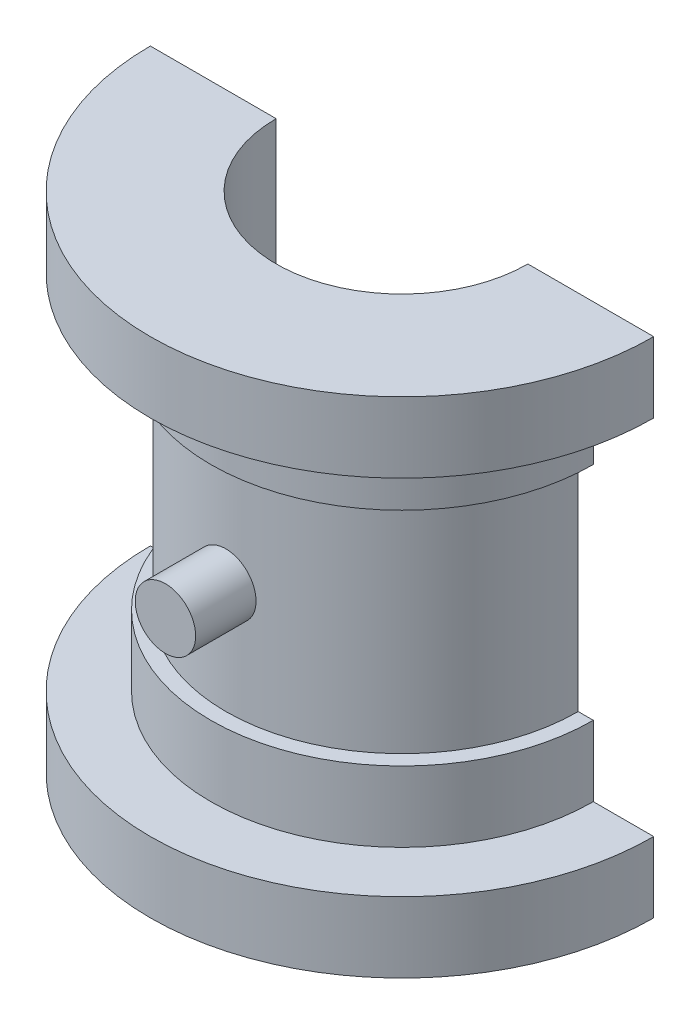
SolidWorks part; units mm, degrees
ref_plane "Front Plane" through (0, 0, 0) normal (0, 0, 1) x (1, 0, 0)
ref_plane "Top Plane" through (0, 0, 0) normal (0, 1, 0) x (1, 0, 0)
ref_plane "Right Plane" through (0, 0, 0) normal (1, 0, 0) x (0, 0, -1)
sketch "Sketch1" plane through (0, 0, 0) normal (0, 0, 1) x (1, 0, 0)
  line L0 (0, 26.2618) -> (0, -29.5741) construction
  line L1 (-37.224, 0) -> (43.2177, 0) construction
  line L2 (12.5, 25) -> (12.5, -25)
  line L3 (12.5, -25) -> (25, -25)
  line L4 (25, -25) -> (25, -18)
  line L5 (25, -18) -> (19, -18)
  line L6 (19, -18) -> (19, -11)
  line L7 (19, -11) -> (17.5, -11)
  line L8 (17.5, -11) -> (17.5, 11)
  line L9 (19, 11) -> (17.5, 11)
  line L10 (19, 18) -> (19, 11)
  line L11 (25, 18) -> (19, 18)
  line L12 (25, 25) -> (25, 18)
  line L13 (12.5, 25) -> (25, 25)
  point P14 (17.5, 0)
  point P15 (12.5, 0)
  dimension "D1" = 25
  dimension "D2" = 18
  dimension "D3" = 11
  dimension "D4" = 25
  dimension "D5" = 19
  dimension "D6" = 17.5
  dimension "D7" = 12.5
revolve "Revolve1" add sketch "Sketch1" angle 360 about L0
sketch "Sketch2" plane through (0, 25, 0) normal (0, 1, 0) x (1, 0, 0)
  line L0 (-25, 0) -> (25, 0)
  circle A0 centre (0, 0) radius 25 construction
extrude "Cut-Extrude2" cut sketch "Sketch2" against normal through all and the other way through all
ref_plane "Plane1" through (0, 0, -17.5) normal (0, 0, 1) x (1, 0, 0)
ref_plane "Plane2" through (0, 0, 17.5) normal (0, 0, 1) x (1, 0, 0)
sketch "Sketch4" plane through (0, 0, 17.5) normal (0, 0, 1) x (1, 0, 0)
  circle A0 centre (0, 0) radius 3
  dimension "D1" = 6
extrude "Boss-Extrude1" add sketch "Sketch4" along normal blind 6 separate body
